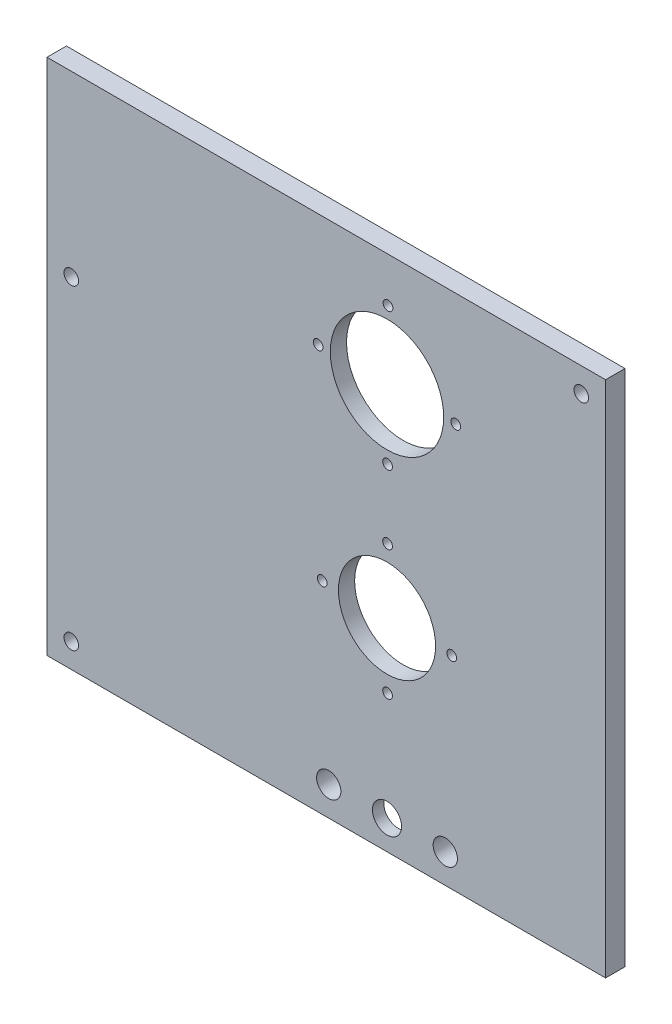
SolidWorks part; units mm, degrees
ref_plane "Plan1" through (0, 0, 0) normal (0, 0, 1) x (1, 0, 0)
ref_plane "Plan2" through (0, 0, 0) normal (0, 1, 0) x (1, 0, 0)
ref_plane "Plan3" through (0, 0, 0) normal (1, 0, 0) x (0, 0, -1)
sketch "Esquisse1" plane through (0, 0, 0) normal (0, 0, 1) x (1, 0, 0)
  line L0 (-140, 40) -> (-140, -280)
  line L1 (-140, -280) -> (205, -280)
  line L2 (-140, 40) -> (205, 40)
  line L3 (205, 40) -> (205, -280)
  circle A0 centre (190, 25) radius 4.5
  circle A1 centre (-125, -265) radius 4.5
  circle A2 centre (70, -155) radius 30
  circle A3 centre (70, -30) radius 35
  circle A4 centre (-125, -70) radius 4.5
  dimension "D3" = 15
  dimension "D4" = 15
  dimension "D5" = 15
  dimension "D8" = 250
  dimension "D11" = 15
  dimension "D13" = 70
  dimension "D14" = 60
  dimension "D15" = 9
  dimension "D16" = 9
  dimension "D17" = 9
  dimension "D1" = 345
  dimension "D2" = 320
  dimension "D6" = 15
  dimension "D7" = 125
  dimension "D9" = 135
  dimension "D10" = 135
  dimension "D12" = 195
extrude "Base-Extrusion" add sketch "Esquisse1" along normal blind 12
sketch "Esquisse2" plane through (0, 0, 0) normal (0, 0, -1) x (-1, 0, 0)
  circle A0 centre (-70, -30) radius 55
  circle A1 centre (-70, -155) radius 47.5
  dimension "D1" = 110
  dimension "D2" = 95
extrude "Enlèv. mat.-Extru.1" cut sketch "Esquisse2" against normal blind 2
hole_wizard "Perçage3" positions "Esquisse7" profile "Esquisse6" tap size "M6x1.0" standard "ISO"
sketch "Esquisse7" plane through (0, 0, 12) normal (0, 0, 1) x (1, 0, 0)
  circle A0 centre (70, -30) radius 35 construction
  circle A1 centre (70, -155) radius 30 construction
  point P0 (70.6097, 12.5)
  point P1 (70.3589, -72.5)
  point P2 (112.5, -30)
  point P3 (27.5, -30)
  point P4 (110, -155)
  point P5 (70.3589, -195)
  point P6 (30, -155)
  point P7 (70.3589, -115)
  dimension "D1" = 42.5
  dimension "D4" = 42.5
  dimension "D5" = 40
  dimension "D6" = 40
  dimension "D2" = 42.5
  dimension "D3" = 42.5
  dimension "D7" = 40
  dimension "D8" = 40
sketch "Esquisse6" plane through (70.6097, 12.5, 12) normal (1, 0, 0) x (0, -1, 0)
  line L0 (0, 0) -> (0, 12)
  line L1 (0, 12) -> (3, 12)
  line L2 (3, 12) -> (3, 0)
  line L5 (3, 0) -> (0, 0)
  line L11 (0, -6.35) -> (0, 107.95) construction
  dimension "Diamètre du perçage jusqu'au prochain" = 6
  dimension "Profondeur du perçage jusqu'au prochain" = 12
sketch "Esquisse8" plane through (0, 0, 12) normal (0, 0, 1) x (1, 0, 0)
  line L0 (205, -280) -> (205, 40) construction
  line L1 (-140, -280) -> (205, -280) construction
  circle A0 centre (70, -262) radius 9
  circle A1 centre (34, -262) radius 7.5
  circle A2 centre (106, -262) radius 7.5
  dimension "D1" = 135
  dimension "D2" = 18
  dimension "D3" = 18
  dimension "D4" = 15
  dimension "D5" = 15
  dimension "D6" = 36
  dimension "D7" = 72
extrude "Enlèv. mat.-Extru.2" cut sketch "Esquisse8" against normal through all
sketch "Esquisse9" plane through (0, 0, 0) normal (0, 0, -1) x (-1, 0, 0)
  line L0 (-52, -262) -> (-52, -280)
  line L1 (-88, -262) -> (-88, -280)
  line L2 (140, -280) -> (-205, -280) construction
  line L3 (-88, -280) -> (-52, -280)
  arc A0 (-52, -262) -> (-88, -262) centre (-70, -262) ccw
  circle A1 centre (-70, -262) radius 9 construction
  dimension "D1" = 36
extrude "Enlèv. mat.-Extru.3" cut sketch "Esquisse9" against normal blind 5
